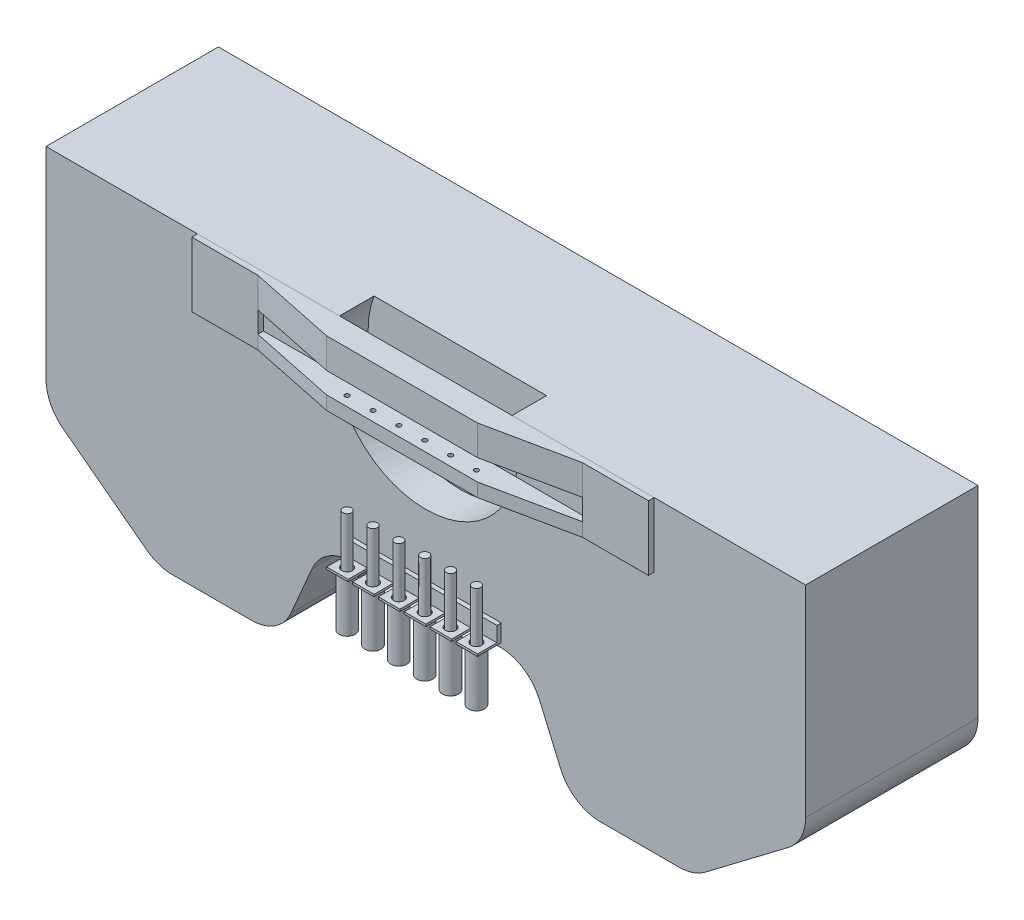
SolidWorks part; units mm, degrees
ref_plane "Front Plane" through (0, 0, 0) normal (0, 0, 1) x (1, 0, 0)
ref_plane "Top Plane" through (0, 0, 0) normal (0, 1, 0) x (1, 0, 0)
ref_plane "Right Plane" through (0, 0, 0) normal (1, 0, 0) x (0, 0, -1)
sketch "Sketch1" plane through (0, 0, 0) normal (0, 0, 1) x (1, 0, 0)
  line L0 (-17.2052, 0) -> (17.2052, 0)
  line L1 (26.3916, -6.0489) -> (31.277, -17.4075)
  line L2 (40.4633, -23.4564) -> (58.7681, -23.4564)
  line L3 (64.8052, -21.4285) -> (84.143, -6.7843)
  line L4 (88.1059, 1.1877) -> (88.1059, 47.9217)
  line L5 (0, 0) -> (0, 40.3551) construction
  line L6 (-88.1059, 1.1877) -> (-88.1059, 47.9217)
  line L7 (-64.8052, -21.4285) -> (-84.143, -6.7843)
  line L8 (-40.4633, -23.4564) -> (-58.7681, -23.4564)
  line L9 (-26.3916, -6.0489) -> (-31.277, -17.4075)
  line L10 (-88.1059, 47.9217) -> (88.1059, 47.9217)
  arc A0 (84.143, -6.7843) -> (88.1059, 1.1877) centre (78.1059, 1.1877) ccw
  arc A1 (58.7681, -23.4564) -> (64.8052, -21.4285) centre (58.7681, -13.4564) ccw
  arc A2 (31.277, -17.4075) -> (40.4633, -23.4564) centre (40.4633, -13.4564) ccw
  arc A3 (17.2052, 0) -> (26.3916, -6.0489) centre (17.2052, -10) cw
  arc A4 (-17.2052, 0) -> (-26.3916, -6.0489) centre (-17.2052, -10) ccw
  arc A5 (-84.143, -6.7843) -> (-88.1059, 1.1877) centre (-78.1059, 1.1877) cw
  arc A6 (-58.7681, -23.4564) -> (-64.8052, -21.4285) centre (-58.7681, -13.4564) cw
  arc A7 (-40.4633, -23.4564) -> (-31.277, -17.4075) centre (-40.4633, -13.4564) ccw
  point P15 (88.1059, -3.7833)
  point P18 (62.1273, -23.4564)
  point P21 (33.8787, -23.4564)
  point P24 (23.7899, 0)
  point P27 (-23.7899, 0)
  point P30 (-88.1059, -3.7833)
  point P33 (-62.1273, -23.4564)
  point P36 (-33.8787, -23.4564)
  dimension "D1" = 10
  dimension "D2" = 10
extrude "Boss-Extrude1" add sketch "Sketch1" along normal blind 40
sketch "Sketch2" plane through (0, 0, 40) normal (0, 0, 1) x (1, 0, 0)
  line L0 (-17.2052, 0) -> (17.2052, 0) construction
  line L1 (-17.5, 5) -> (-12.5, 5)
  line L2 (-17.5, 5) -> (-17.5, 1)
  line L3 (-17.5, 1) -> (-12.5, 1)
  line L4 (-12.5, 5) -> (-12.5, 1)
  line L5 (-11.5, 5) -> (-6.5, 5)
  line L6 (-11.5, 5) -> (-11.5, 1)
  line L7 (-11.5, 1) -> (-6.5, 1)
  line L8 (-6.5, 5) -> (-6.5, 1)
  line L9 (-5.5, 5) -> (-0.5, 5)
  line L10 (-5.5, 5) -> (-5.5, 1)
  line L11 (-5.5, 1) -> (-0.5, 1)
  line L12 (-0.5, 5) -> (-0.5, 1)
  line L13 (0, 0) -> (0, 14.9516) construction
  line L14 (0.5, 5) -> (0.5, 1)
  line L15 (5.5, 1) -> (0.5, 1)
  line L16 (5.5, 5) -> (5.5, 1)
  line L17 (5.5, 5) -> (0.5, 5)
  line L18 (6.5, 5) -> (6.5, 1)
  line L19 (11.5, 1) -> (6.5, 1)
  line L20 (11.5, 5) -> (11.5, 1)
  line L21 (11.5, 5) -> (6.5, 5)
  line L22 (12.5, 5) -> (12.5, 1)
  line L23 (17.5, 1) -> (12.5, 1)
  line L24 (17.5, 5) -> (17.5, 1)
  line L25 (17.5, 5) -> (12.5, 5)
  dimension "D1" = 5
  dimension "D2" = 5
  dimension "D3" = 5
  dimension "D4" = 0.5
  dimension "D5" = 1
  dimension "D6" = 1
  dimension "D7" = 1
  dimension "D8" = 4
extrude "Boss-Extrude2" add sketch "Sketch2" along normal blind 1
sketch "Sketch3" plane through (0, 0, 41) normal (0, 0, 1) x (1, 0, 0)
  line L0 (-12.5, 1) -> (-12.5, 5) construction
  line L1 (-17.5, 1) -> (-12.5, 1)
  line L2 (-17.5, 1) -> (-17.5, 1.5)
  line L3 (-17.5, 1.5) -> (-12.5, 1.5)
  line L4 (-12.5, 1) -> (-12.5, 1.5)
  line L5 (-11.5, 1) -> (-6.5, 1)
  line L6 (-11.5, 1.5) -> (-6.5, 1.5)
  line L7 (-11.5, 1) -> (-11.5, 1.5)
  line L8 (-6.5, 1) -> (-6.5, 1.5)
  line L9 (-5.5, 1) -> (-0.5, 1)
  line L10 (-5.5, 1.5) -> (-0.5, 1.5)
  line L11 (-5.5, 1) -> (-5.5, 1.5)
  line L12 (-0.5, 1) -> (-0.5, 1.5)
  line L13 (0.5, 1) -> (5.5, 1)
  line L14 (0.5, 1.5) -> (5.5, 1.5)
  line L15 (0.5, 1) -> (0.5, 1.5)
  line L16 (5.5, 1) -> (5.5, 1.5)
  line L17 (6.5, 1) -> (11.5, 1)
  line L18 (6.5, 1.5) -> (11.5, 1.5)
  line L19 (6.5, 1) -> (6.5, 1.5)
  line L20 (11.5, 1) -> (11.5, 1.5)
  line L21 (12.5, 1) -> (17.5, 1)
  line L22 (12.5, 1.5) -> (17.5, 1.5)
  line L23 (12.5, 1) -> (12.5, 1.5)
  line L24 (17.5, 1) -> (17.5, 1.5)
  dimension "D1" = 0.5
extrude "Boss-Extrude3" add sketch "Sketch3" along normal blind 4.5
sketch "Sketch4" plane through (0, 1, 0) normal (0, -1, 0) x (1, 0, 0)
  line L0 (12.5, 41) -> (17.5, 45.5) construction
  circle A0 centre (15, 43.25) radius 1.25
  circle A1 centre (9, 43.25) radius 1.25
  circle A2 centre (3, 43.25) radius 1.25
  circle A3 centre (-3, 43.25) radius 1.25
  circle A4 centre (-9, 43.25) radius 1.25
  circle A5 centre (-15, 43.25) radius 1.25
  dimension "D1" = 2.5
extrude "Cut-Extrude1" cut sketch "Sketch4" against normal blind 4
sketch "Sketch5" plane through (0, 47.9217, 0) normal (0, 1, 0) x (1, 0, 0)
  line L0 (0, 0) -> (0, -71.5387) construction
  line L1 (52.9682, -40) -> (52.9682, -41.2964)
  line L2 (88.1059, -40) -> (-88.1059, -40) construction
  line L3 (52.9682, -41.2964) -> (37.6668, -41.2964)
  line L4 (37.6668, -41.2964) -> (17.5, -45.5)
  line L5 (17.5, -45.5) -> (-17.5, -45.5)
  line L6 (52.9682, -40) -> (-52.9682, -40)
  line L7 (-37.6668, -41.2964) -> (-17.5, -45.5)
  line L8 (-52.9682, -41.2964) -> (-37.6668, -41.2964)
  line L9 (-52.9682, -40) -> (-52.9682, -41.2964)
  point P12 (0, -40)
  point P13 (0, -45.5)
  point P15 (17.5, -45.5)
extrude "Boss-Extrude4" add sketch "Sketch5" against normal blind 15 separate body
sketch "Sketch6" plane through (0, 0, 40) normal (0, 0, 1) x (1, 0, 0)
  line L0 (0, 47.9217) -> (0, 32.9217) construction
  line L1 (-17.5, 47.9217) -> (17.5, 47.9217) construction
  line L2 (-17.5, 32.9217) -> (17.5, 32.9217) construction
  circle A0 centre (0, 40.4217) radius 21.3746
extrude "Cut-Extrude2" cut sketch "Sketch6" against normal blind 8
sketch "Sketch7" plane through (0, 0, 45.5) normal (0, 0, 1) x (1, 0, 0)
  line L0 (37.6668, 32.9217) -> (37.6668, 47.9217) construction
  line L1 (-37.6668, 36.0549) -> (37.6668, 36.0549)
  line L2 (-37.6668, 36.0549) -> (-37.6668, 40.9544)
  line L3 (-37.6668, 40.9544) -> (37.6668, 40.9544)
  line L4 (37.6668, 36.0549) -> (37.6668, 40.9544)
  line L5 (-37.6668, 36.0549) -> (37.6668, 40.9544) construction
  line L6 (-37.6668, 40.9544) -> (37.6668, 36.0549) construction
  point P0 (0, 38.5047)
  point P7 (37.6668, 40.9544)
extrude "Cut-Extrude3" cut sketch "Sketch7" against normal up to next (5.5 mm away)
sketch "Sketch8" plane through (0, 32.9217, 0) normal (0, -1, 0) x (1, 0, 0)
  circle A0 centre (15, 43.25) radius 0.531
  circle A1 centre (9, 43.25) radius 0.531
  circle A2 centre (3, 43.25) radius 0.531
  circle A3 centre (-3, 43.25) radius 0.531
  circle A4 centre (-9, 43.25) radius 0.531
  circle A5 centre (-15, 43.25) radius 0.531
extrude "Cut-Extrude4" cut sketch "Sketch8" against normal blind 6
sketch "Sketch9" plane through (0, 1, 0) normal (0, -1, 0) x (1, 0, 0)
  circle A0 centre (15, 43.25) radius 1.8626
  circle A1 centre (9, 43.25) radius 1.8626
  circle A2 centre (3, 43.25) radius 1.8626
  circle A3 centre (-3, 43.25) radius 1.8626
  circle A4 centre (-9, 43.25) radius 1.8626
  circle A5 centre (-15, 43.25) radius 1.8626
extrude "Boss-Extrude5" add sketch "Sketch9" along normal blind 12
sketch "Sketch10" plane through (0, 1, 0) normal (0, 1, 0) x (1, 0, 0)
  circle A0 centre (15, -43.25) radius 0.9953
  circle A1 centre (9, -43.25) radius 0.9953
  circle A2 centre (3, -43.25) radius 0.9953
  circle A3 centre (-3, -43.25) radius 0.9953
  circle A4 centre (-9, -43.25) radius 0.9953
  circle A5 centre (-15, -43.25) radius 0.9953
extrude "Boss-Extrude6" add sketch "Sketch10" along normal blind 12
